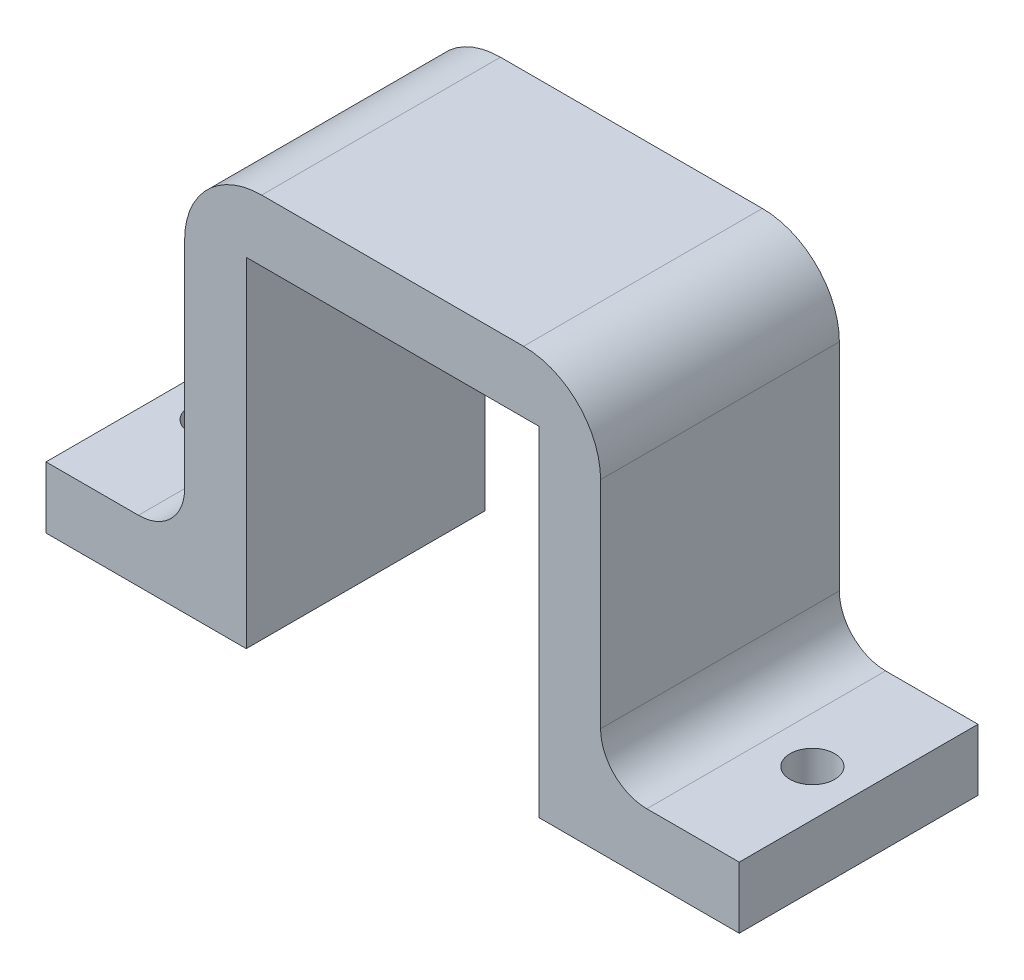
SolidWorks part; units mm, degrees
ref_plane "Front Plane" through (0, 0, 0) normal (0, 0, 1) x (1, 0, 0)
ref_plane "Top Plane" through (0, 0, 0) normal (0, 1, 0) x (1, 0, 0)
ref_plane "Right Plane" through (0, 0, 0) normal (1, 0, 0) x (0, 0, -1)
sketch "Sketch1" plane through (0, 0, 0) normal (0, 0, 1) x (1, 0, 0)
  line L0 (0, 3) -> (0, 17)
  line L1 (5, 22) -> (22, 22)
  line L2 (27, 17) -> (27, 3)
  line L3 (30, 0) -> (36, 0)
  line L4 (36, 0) -> (36, -4)
  line L5 (36, -4) -> (23, -4)
  line L6 (23, -4) -> (23, 18)
  line L7 (23, 18) -> (4, 18)
  line L8 (4, 18) -> (4, -4)
  line L9 (4, -4) -> (-9, -4)
  line L10 (-9, -4) -> (-9, 0)
  line L11 (-9, 0) -> (-3, 0)
  arc A0 (5, 22) -> (0, 17) centre (5, 17) ccw
  arc A1 (22, 22) -> (27, 17) centre (22, 17) cw
  arc A2 (0, 3) -> (-3, 0) centre (-3, 3) cw
  arc A3 (30, 0) -> (27, 3) centre (30, 3) cw
  point P18 (27, 22)
  point P21 (0, 0)
  dimension "D10" = 5
  dimension "D11" = 3
  dimension "D1" = 19
  dimension "D2" = 4
  dimension "D3" = 4
  dimension "D4" = 4
  dimension "D5" = 4
  dimension "D6" = 4
  dimension "D7" = 22
  dimension "D8" = 13
  dimension "D9" = 13
extrude "Boss-Extrude1" add sketch "Sketch1" along normal blind 23
ref_plane "Plane1" through (13.5, 0, 0) normal (1, 0, 0) x (0, 0, -1)
sketch "Sketch3" plane through (0, 0, 0) normal (0, 1, 0) x (1, 0, 0)
  line L0 (-9, -11.5) -> (36, -11.5) construction
  line L1 (-9, -23) -> (-9, 0) construction
  line L2 (36, -23) -> (36, 0) construction
  line L3 (13.5, -12.1) -> (13.5, 12.1) construction
  line L4 (36, 0) -> (30, 0) construction
  line L6 (36, -23) -> (30, -23) construction
  circle A0 centre (-6, -2.25) radius 1.45
  circle A1 centre (-6, -20.75) radius 1.45
  circle A2 centre (33, -20.75) radius 1.45
  circle A3 centre (33, -2.25) radius 1.45
  point P23 (33, -23)
  dimension "D1" = 2.9
  dimension "D2" = 2.25
  dimension "D3" = 2.25
sketch "Sketch4" plane through (0, 0, 0) normal (-1, 0, 0) x (0, 0, 1)
  line L0 (23, 17) -> (0, 17) construction
  line L1 (4, 17) -> (7.5, 17)
  line L2 (4, 17) -> (4, -4)
  line L3 (4, -4) -> (7.5, -4)
  line L4 (7.5, 17) -> (7.5, -4)
  line L5 (23, -4) -> (0, -4) construction
  line L7 (0, 0) -> (0, -4) construction
  dimension "D1" = 4
  dimension "D2" = 3.5
extrude "Cut-Extrude2" cut sketch "Sketch4" against normal blind 10 and the other way blind 23
sketch "Sketch5" plane through (0, 22, 0) normal (0, 1, 0) x (1, 0, 0)
  line L0 (-9, -7.5) -> (36, -7.5) construction
  line L1 (36, -23) -> (36, 0) construction
  line L3 (-9, 0) -> (36, 0)
  line L4 (-9, 0) -> (-9, -7.5)
  line L5 (-9, -7.5) -> (36, -7.5)
  line L6 (36, 0) -> (36, -7.5)
extrude "Cut-Extrude3" cut sketch "Sketch5" against normal blind 26
sketch "Sketch7" plane through (0, 0, 0) normal (0, 1, 0) x (1, 0, 0)
  line L0 (13.5, -8.525) -> (13.5, 8.525) construction
  line L3 (-3, -23) -> (-9, -23) construction
  line L5 (36, -7.5) -> (30, -7.5) construction
  circle A0 centre (-6, -15.25) radius 1.45
  circle A1 centre (33, -15.25) radius 1.45
  point P12 (0, 0)
  point P13 (0, 0)
  point P14 (-6, -23)
  dimension "D1" = 2.9
  dimension "D2" = 7.75
extrude "Cut-Extrude4" cut sketch "Sketch7" against normal blind 26
